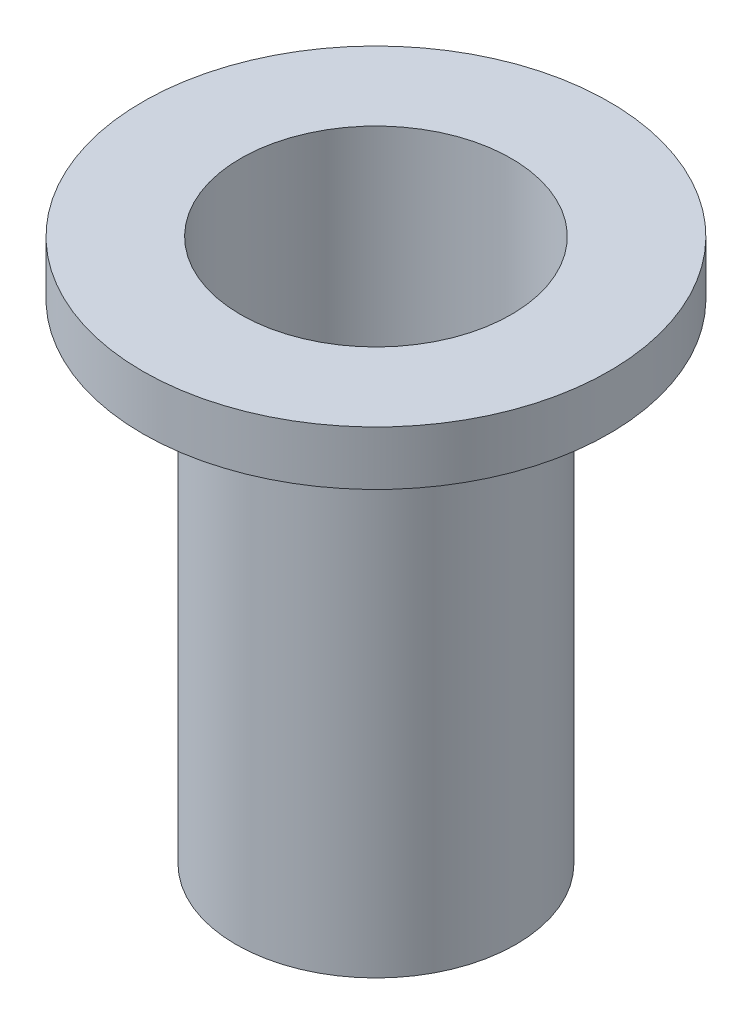
SolidWorks part; units mm, degrees
ref_plane "Front Plane" through (0, 0, 0) normal (0, 0, 1) x (1, 0, 0)
ref_plane "Top Plane" through (0, 0, 0) normal (0, 1, 0) x (1, 0, 0)
ref_plane "Right Plane" through (0, 0, 0) normal (1, 0, 0) x (0, 0, -1)
sketch "Sketch1" plane through (0, 0, 0) normal (0, 1, 0) x (1, 0, 0)
  circle A0 centre (0, 0) radius 1.45
  circle A1 centre (0, 0) radius 1.5
  dimension "D1" = 2.9
  dimension "D2" = 3
extrude "Boss-Extrude1" add sketch "Sketch1" along normal blind 5.24
sketch "Sketch4" plane through (0, 5.24, 0) normal (0, 1, 0) x (1, 0, 0)
  circle A0 centre (0, 0) radius 1.45
  circle A1 centre (0, 0) radius 2.5
  dimension "D1" = 2.9
  dimension "D2" = 5
extrude "Boss-Extrude2" add sketch "Sketch4" along normal blind 0.58
